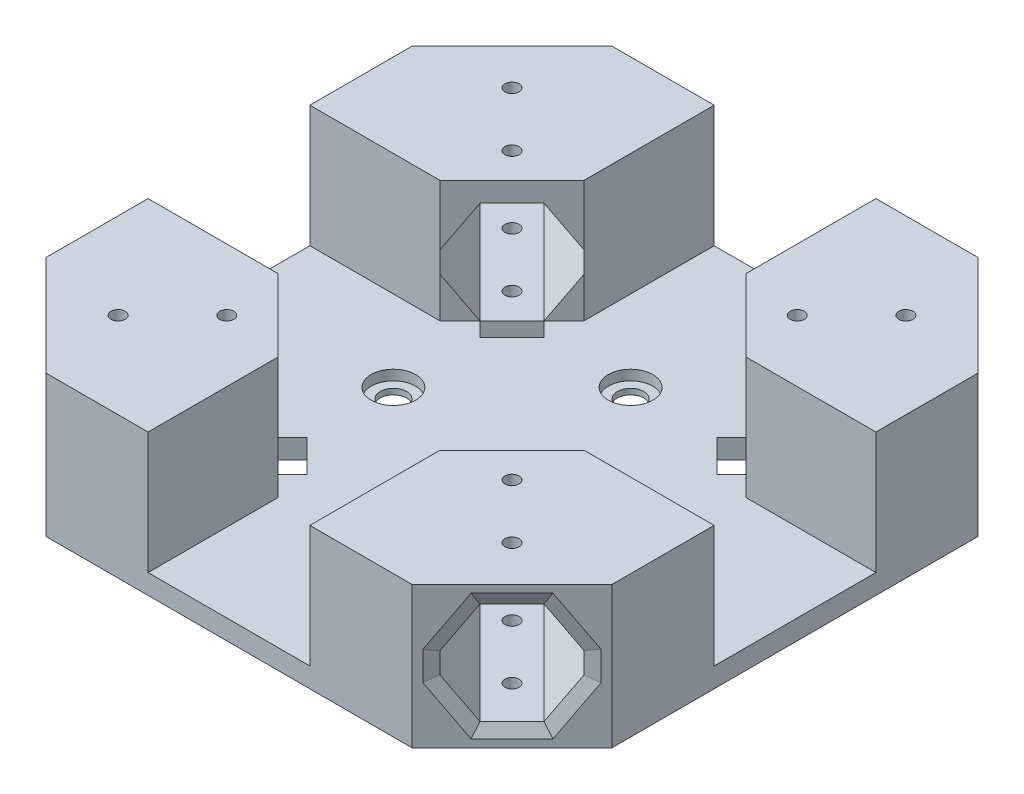
SolidWorks part; units mm, degrees
material "ABS generico"
ref_plane "Piano frontale" through (0, 0, 0) normal (0, 0, 1) x (1, 0, 0)
ref_plane "Piano superiore" through (0, 0, 0) normal (0, 1, 0) x (1, 0, 0)
ref_plane "Piano destro" through (0, 0, 0) normal (1, 0, 0) x (0, 0, -1)
sketch "Schizzo1" plane through (0, 0, 0) normal (0, 1, 0) x (1, 0, 0)
  line L0 (-28.0306, -6.8944) -> (-3.2818, -31.6431)
  line L1 (-28.0306, 108.3569) -> (111.9694, 108.3569) construction
  line L2 (-28.0306, 108.3569) -> (-28.0306, -31.6431) construction
  line L3 (-28.0306, -31.6431) -> (111.9694, -31.6431) construction
  line L4 (111.9694, 108.3569) -> (111.9694, -31.6431) construction
  line L5 (87.2207, -31.6431) -> (111.9694, -6.8944)
  line L6 (111.9694, 83.6081) -> (87.2207, 108.3569)
  line L7 (-28.0306, 83.6081) -> (-3.2818, 108.3569)
  line L8 (111.9694, 83.6081) -> (111.9694, -6.8944)
  line L9 (87.2207, -31.6431) -> (-3.2818, -31.6431)
  line L10 (-28.0306, -6.8944) -> (-28.0306, 83.6081)
  line L11 (-3.2818, 108.3569) -> (87.2207, 108.3569)
  dimension "D1" = 140
  dimension "D2" = 140
  dimension "D3" = 45
  dimension "D4" = 45
  dimension "D5" = 45
  dimension "D6" = 35
extrude "Estrusione-Estrusione2" add sketch "Schizzo1" along normal blind 35
sketch "Schizzo2" plane through (0, 35, 0) normal (0, 1, 0) x (1, 0, 0)
  line L0 (87.2207, 108.3569) -> (-3.2818, 108.3569) construction
  line L1 (21.9694, 108.3569) -> (61.9694, 108.3569)
  line L2 (21.9694, 108.3569) -> (21.9694, -31.6431)
  line L3 (21.9694, -31.6431) -> (61.9694, -31.6431)
  line L4 (61.9694, 108.3569) -> (61.9694, -31.6431)
  line L5 (-3.2818, -31.6431) -> (87.2207, -31.6431) construction
  line L7 (-28.0306, 83.6081) -> (-28.0306, -6.8944) construction
  line L8 (111.9694, -6.8944) -> (111.9694, 83.6081) construction
  line L10 (-28.0306, 58.3569) -> (111.9694, 58.3569)
  line L11 (-28.0306, 58.3569) -> (-28.0306, 18.3569)
  line L12 (-28.0306, 18.3569) -> (111.9694, 18.3569)
  line L13 (111.9694, 58.3569) -> (111.9694, 18.3569)
  line M1 (-28.0306, 83.6081) -> (-28.0306, -6.8944)
  line M3 (-3.2818, -31.6431) -> (87.2207, -31.6431)
  line M5 (111.9694, -6.8944) -> (111.9694, 83.6081)
  line M7 (87.2207, 108.3569) -> (-3.2818, 108.3569)
  dimension "D1" = 40
  dimension "D2" = 50
  dimension "D3" = 50
extrude "Taglio-Estrusione1" cut sketch "Schizzo2" against normal blind 30.1 contours L4 L12 L10 M5 | L2 L12 L4 L10 | L2 L10 L4 M7 | L12 L2 L10 M1 | L12 L2 L4 M3
sketch "Schizzo3" plane through (59.4319, 0, 59.4319) normal (0.7071, 0, 0.7071) x (0.7071, 0, -0.7071)
  line L0 (56.7993, 30.1) -> (56.7993, 4.9) construction
  line L1 (51.1993, 30.1) -> (62.3993, 30.1)
  line L3 (51.1993, 4.9) -> (62.3993, 4.9)
  line L6 (44.1993, 20.1) -> (44.1993, 14.9)
  line L8 (69.3993, 20.1) -> (69.3993, 14.9)
  line L9 (44.1993, 17.5) -> (69.3993, 17.5) construction
  line L10 (62.3993, 30.1) -> (69.3993, 20.1)
  line L11 (69.3993, 14.9) -> (62.3993, 4.9)
  line L12 (51.1993, 4.9) -> (44.1993, 14.9)
  line L13 (44.1993, 20.1) -> (51.1993, 30.1)
  line L14 (39.2993, 35) -> (39.2993, 0) construction
  line L16 (39.2993, 35) -> (74.2993, 35) construction
  dimension "D1" = 11.2
  dimension "D2" = 5.2
  dimension "D3" = 25.2
  dimension "D4" = 25.2
  dimension "D5" = 4.9
  dimension "D6" = 4.9
extrude "Taglio-Estrusione2" cut sketch "Schizzo3" against normal through all
sketch "Schizzo4" plane through (97.7888, 0, -97.7888) normal (0.7071, 0, -0.7071) x (-0.7071, 0, -0.7071)
  line L0 (-20.0545, 35) -> (-20.0545, 0) construction
  line L1 (-8.1545, 30.1) -> (3.0455, 30.1)
  line L3 (-8.1545, 4.9) -> (3.0455, 4.9)
  line L6 (-15.1545, 20.1) -> (-15.1545, 14.9)
  line L8 (10.0455, 20.1) -> (10.0455, 14.9)
  line L9 (-20.0545, 35) -> (14.9455, 35) construction
  line L10 (-15.1545, 20.1) -> (-8.1545, 30.1)
  line L11 (3.0455, 30.1) -> (10.0455, 20.1)
  line L12 (10.0455, 14.9) -> (3.0455, 4.9)
  line L13 (-8.1545, 4.9) -> (-15.1545, 14.9)
  dimension "D1" = 11.2
  dimension "D2" = 5.2
  dimension "D3" = 25.2
  dimension "D4" = 25.2
  dimension "D5" = 4.9
  dimension "D6" = 4.9
extrude "Taglio-Estrusione3" cut sketch "Schizzo4" against normal through all
sketch "Schizzo6" plane through (0, 35, 0) normal (0, 1, 0) x (1, 0, 0)
  line L0 (21.9694, 0.5378) -> (4.1504, 18.3569)
  line L1 (4.1504, 18.3569) -> (21.9694, 18.3569)
  line L2 (21.9694, 18.3569) -> (21.9694, 0.5378)
  line L3 (41.9694, 108.3569) -> (41.9694, -31.6431) construction
  line L4 (61.9694, 108.3569) -> (21.9694, 108.3569) construction
  line L5 (21.9694, -31.6431) -> (61.9694, -31.6431) construction
  line L6 (111.9694, 38.3569) -> (-28.0306, 38.3569) construction
  line L7 (111.9694, 18.3569) -> (111.9694, 58.3569) construction
  line L8 (-28.0306, 58.3569) -> (-28.0306, 18.3569) construction
  line L9 (4.1504, 58.3569) -> (21.9694, 76.176)
  line L10 (21.9694, 76.176) -> (21.9694, 58.3569)
  line L11 (21.9694, 58.3569) -> (4.1504, 58.3569)
  line L12 (61.9694, 76.176) -> (79.7885, 58.3569)
  line L13 (79.7885, 58.3569) -> (61.9694, 58.3569)
  line L14 (61.9694, 58.3569) -> (61.9694, 76.176)
  line L15 (79.7885, 18.3569) -> (61.9694, 0.5378)
  line L16 (61.9694, 0.5378) -> (61.9694, 18.3569)
  line L17 (61.9694, 18.3569) -> (79.7885, 18.3569)
  point P30 (41.9694, 38.3569)
extrude "Taglio-Estrusione4" cut sketch "Schizzo6" against normal blind 30.1
chamfer "Smusso1" distance 3 distance2 1 32 edges at (99.5951, 30.1, 19.2687) (106.0297, 25.1, 12.8341) (108.5046, 17.5, 10.3592) (106.0297, 9.9, 12.8341) (99.5951, 4.9, 19.2687) (93.1604, 9.9, 25.7034) (90.6855, 17.5, 28.1783) (93.1604, 25.1, 25.7034) (-22.0909, 9.9, 12.8341) (-24.5657, 17.5, 10.3592) (-22.0909, 25.1, 12.8341) (-15.6562, 30.1, 19.2687) (-9.2215, 25.1, 25.7034) (-6.7466, 17.5, 28.1783) (-9.2215, 9.9, 25.7034) (-15.6562, 4.9, 19.2687) (-22.0909, 9.9, -89.5478) (-24.5657, 17.5, -87.073) (-22.0909, 25.1, -89.5478) (-15.6562, 30.1, -95.9825) (-9.2215, 25.1, -102.4172) (-6.7466, 17.5, -104.8921) (-9.2215, 9.9, -102.4172) (-15.6562, 4.9, -95.9825) (93.1604, 25.1, -102.4172) (90.6855, 17.5, -104.8921) (93.1604, 9.9, -102.4172) (99.5951, 4.9, -95.9825) (106.0297, 9.9, -89.5478) (108.5046, 17.5, -87.073) (99.5951, 30.1, -95.9825) (106.0297, 25.1, -89.5478)
sketch "Schizzo7" plane through (0, 4.9, 0) normal (0, 1, 0) x (1, 0, 0)
  line L0 (41.9694, 108.3569) -> (41.9694, -31.6431) construction
  line L1 (9.1001, 13.4071) -> (17.0197, 5.4875)
  line L2 (9.1001, 13.4071) -> (12.6356, 16.9427)
  line L3 (12.6356, 16.9427) -> (20.5552, 9.0231)
  line L4 (17.0197, 5.4875) -> (20.5552, 9.0231)
  line L5 (61.9694, 108.3569) -> (21.9694, 108.3569) construction
  line L6 (21.9694, -31.6431) -> (61.9694, -31.6431) construction
  line L7 (111.9694, 38.3569) -> (-28.0306, 38.3569) construction
  line L8 (111.9694, 18.3569) -> (111.9694, 58.3569) construction
  line L9 (-28.0306, 58.3569) -> (-28.0306, 18.3569) construction
  line L10 (17.0197, 71.2262) -> (9.1001, 63.3066)
  line L11 (17.0197, 71.2262) -> (20.5552, 67.6907)
  line L12 (20.5552, 67.6907) -> (12.6356, 59.7711)
  line L13 (9.1001, 63.3066) -> (12.6356, 59.7711)
  line L14 (74.8388, 63.3066) -> (66.9192, 71.2262)
  line L15 (74.8388, 63.3066) -> (71.3033, 59.7711)
  line L16 (71.3033, 59.7711) -> (63.3837, 67.6907)
  line L17 (66.9192, 71.2262) -> (63.3837, 67.6907)
  line L18 (66.9192, 5.4875) -> (74.8388, 13.4071)
  line L19 (66.9192, 5.4875) -> (63.3837, 9.0231)
  line L20 (63.3837, 9.0231) -> (71.3033, 16.9427)
  line L21 (74.8388, 13.4071) -> (71.3033, 16.9427)
  point P35 (41.9694, 38.3569)
  dimension "D1" = 5
  dimension "D2" = 4
extrude "Taglio-Estrusione5" cut sketch "Schizzo7" against normal through all
sketch "Schizzo9" plane through (0, 35, 0) normal (0, 1, 0) x (1, 0, 0)
  line L0 (99.5951, -19.2687) -> (-15.6562, 95.9825) construction
  line L3 (87.2207, -31.6431) -> (111.9694, -6.8944) construction
  line L6 (-3.2818, 108.3569) -> (-28.0306, 83.6081) construction
  line L7 (99.5951, 95.9825) -> (-15.6562, -19.2687) construction
  line L8 (111.9694, 83.6081) -> (87.2207, 108.3569) construction
  line L9 (-28.0306, -6.8944) -> (-3.2818, -31.6431) construction
  circle A0 centre (90.678, 87.0654) radius 1.75
  circle A1 centre (77.243, 73.6304) radius 1.75
  circle A2 centre (90.678, -10.3517) radius 1.75
  circle A3 centre (77.243, 3.0834) radius 1.75
  circle A4 centre (-6.7391, -10.3517) radius 1.75
  circle A5 centre (6.6959, 3.0834) radius 1.75
  circle A6 centre (-6.7391, 87.0654) radius 1.75
  circle A7 centre (6.6959, 73.6304) radius 1.75
  circle A10 centre (6.6959, 73.6304) radius 1.75 construction
  circle A11 centre (-6.7391, 87.0654) radius 1.75 construction
  point P33 (41.9694, 38.3569)
  dimension "D1" = 3.5
  dimension "D2" = 3.5
  dimension "D3" = 4
extrude "Taglio-Estrusione6" cut sketch "Schizzo9" against normal through all
sketch "Schizzo10" plane through (0, 0, 0) normal (0, -1, 0) x (1, 0, 0)
  line L0 (41.9694, -67.6907) -> (41.9694, -9.0231) construction
  line L1 (12.6356, -38.3569) -> (71.3033, -38.3569) construction
  line L2 (111.9694, 6.8944) -> (111.9694, -83.6081) construction
  line L3 (12.6356, -59.7711) -> (12.6356, -38.3569) construction
  line L4 (12.6356, -38.3569) -> (12.6356, -16.9427) construction
  line L5 (20.5552, -9.0231) -> (41.9694, -9.0231) construction
  line L6 (41.9694, -9.0231) -> (63.3837, -9.0231) construction
  circle A0 centre (71.3033, -38.3569) radius 3.25
  circle A1 centre (12.6356, -38.3569) radius 3.25
  circle A2 centre (41.9694, -67.6907) radius 3.25
  circle A3 centre (41.9694, -9.0231) radius 3.25
  dimension "D1" = 6.5
extrude "Taglio-Estrusione7" cut sketch "Schizzo10" against normal up to next
chamfer "Smusso2" distance 2 distance2 1 4 edges at (41.9694, 0, -12.2731) (71.3033, 0, -41.6069) (41.9694, 0, -70.9407) (12.6356, 0, -41.6069)
sketch "Schizzo11" plane through (0, 4.9, 0) normal (0, 1, 0) x (1, 0, 0)
  circle A0 centre (41.9694, 9.0231) radius 5.5
  circle A1 centre (71.3033, 38.3569) radius 5.5
  circle A2 centre (12.6356, 38.3569) radius 5.5
  circle A3 centre (41.9694, 67.6907) radius 5.5
  dimension "D1" = 11
extrude "Taglio-Estrusione8" cut sketch "Schizzo11" against normal blind 2.5
